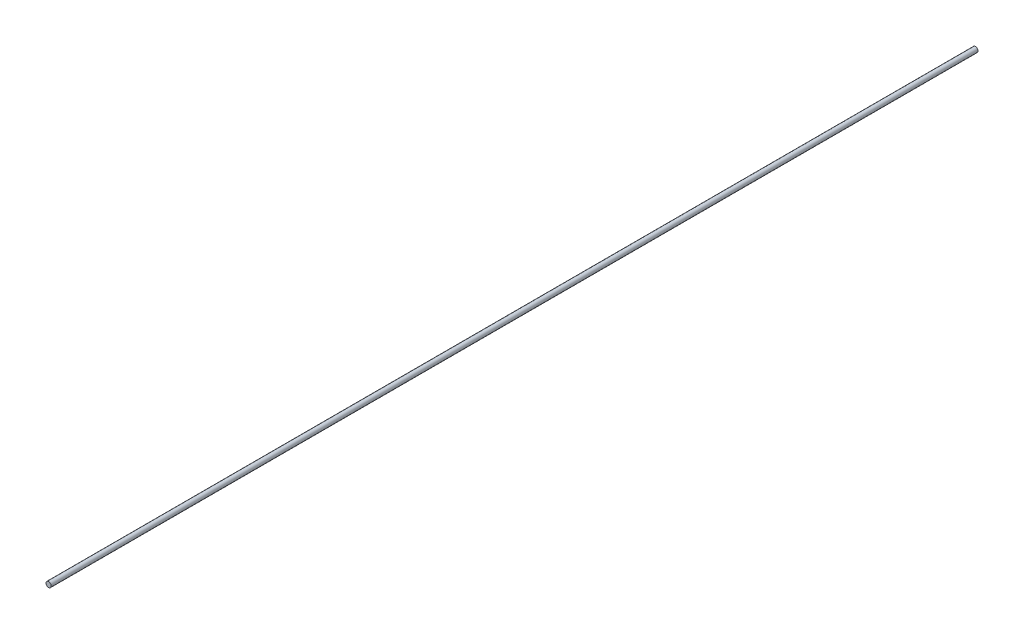
SolidWorks part; units mm, degrees
ref_plane "Front Plane" through (0, 0, 0) normal (0, 0, 1) x (1, 0, 0)
ref_plane "Top Plane" through (0, 0, 0) normal (0, 1, 0) x (1, 0, 0)
ref_plane "Right Plane" through (0, 0, 0) normal (1, 0, 0) x (0, 0, -1)
sketch "Sketch1" plane through (0, 0, 0) normal (0, 0, 1) x (1, 0, 0)
  circle A0 centre (0, 0) radius 1
  dimension "D1" = 2
extrude "Boss-Extrude1" add sketch "Sketch1" along normal blind 360
